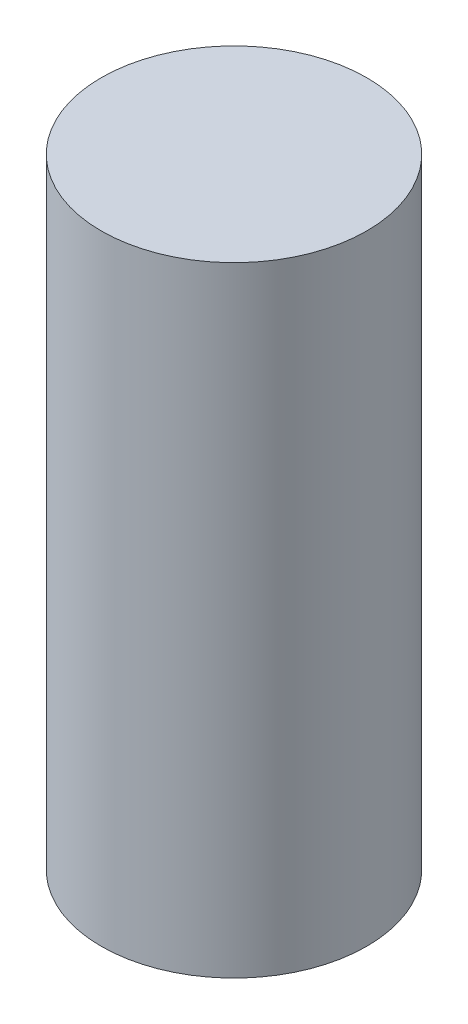
SolidWorks part; units mm, degrees
ref_plane "Front Plane" through (0, 0, 0) normal (0, 0, 1) x (1, 0, 0)
ref_plane "Top Plane" through (0, 0, 0) normal (0, 1, 0) x (1, 0, 0)
ref_plane "Right Plane" through (0, 0, 0) normal (1, 0, 0) x (0, 0, -1)
other "Configuration Table"
sketch "Sketch1" plane through (0, 0, 0) normal (0, 1, 0) x (1, 0, 0)
  circle A0 centre (50, 770) radius 6
extrude "PACK_ayar_mil_3" add sketch "Sketch1" along normal blind 28 from offset 12 separate body
